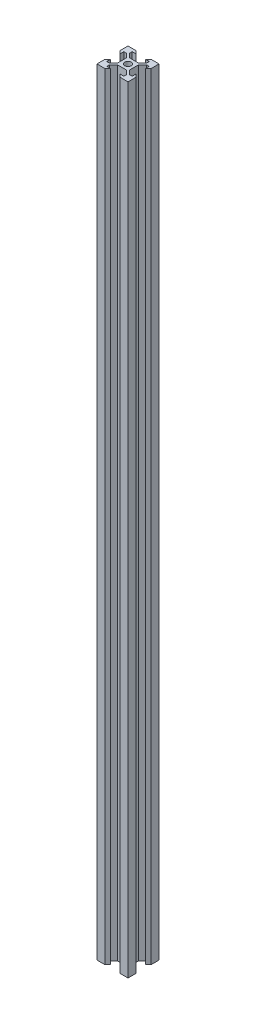
SolidWorks part; units mm, degrees
ref_plane "Front Plane" through (0, 0, 0) normal (0, 0, 1) x (1, 0, 0)
ref_plane "Top Plane" through (0, 0, 0) normal (0, 1, 0) x (1, 0, 0)
ref_plane "Right Plane" through (0, 0, 0) normal (1, 0, 0) x (0, 0, -1)
sketch "Sketch1" plane through (0, 0, 0) normal (0, 1, 0) x (1, 0, 0)
  line L0 (3.9007, 2.84) -> (2.84, 3.9007) construction
  line L1 (-10, -10) -> (10, -10) construction
  line L2 (-10, -10) -> (-10, 10) construction
  line L3 (-10, 10) -> (10, 10) construction
  line L4 (10, -10) -> (10, 10) construction
  line L5 (-10, -10) -> (10, 10) construction
  line L6 (-10, 10) -> (10, -10) construction
  line L7 (-2.84, -2.84) -> (2.84, -2.84) construction
  line L8 (-2.84, -2.84) -> (-2.84, 2.84) construction
  line L9 (-2.84, 2.84) -> (2.84, 2.84) construction
  line L10 (2.84, -2.84) -> (2.84, 2.84) construction
  line L11 (-2.84, -2.84) -> (2.84, 2.84) construction
  line L12 (-2.84, 2.84) -> (2.84, -2.84) construction
  line L13 (2.84, -3.9007) -> (3.9007, -2.84) construction
  line L14 (-3.9007, -2.84) -> (-2.84, -3.9007) construction
  line L15 (-2.84, 3.9007) -> (-3.9007, 2.84) construction
  line L16 (-3.1, 10) -> (3.1, 10) construction
  line L17 (-3.1, 10) -> (-3.1, 8.2) construction
  line L18 (-3.1, 8.2) -> (-4.9, 10)
  line L19 (3.1, 8.2) -> (3.1, 10) construction
  line L20 (-3.1, 8.2) -> (-8.2, 8.2) construction
  line L21 (-2.84, 3.9007) -> (-7.1393, 8.2) construction
  line L22 (-5.4993, 8.2) -> (-5.4993, 6.56)
  line L23 (-4.9, 10) -> (-10, 10)
  line L24 (-3.9007, -3.9007) -> (3.9007, -3.9007) construction
  line L25 (-3.9007, -3.9007) -> (-3.9007, 3.9007) construction
  line L26 (-3.9007, 3.9007) -> (3.9007, 3.9007) construction
  line L27 (3.9007, -3.9007) -> (3.9007, 3.9007) construction
  line L28 (-3.9007, -3.9007) -> (3.9007, 3.9007) construction
  line L29 (-3.9007, 3.9007) -> (3.9007, -3.9007) construction
  line L30 (-5.4993, 6.56) -> (-2.84, 3.9007)
  line L31 (-2.84, 3.9007) -> (0, 3.9007)
  line L32 (-5.4993, 8.2) -> (-3.1, 8.2)
  line L33 (-3.9007, 2.84) -> (-3.9007, 0)
  line L34 (-6.56, 5.4993) -> (-3.9007, 2.84)
  line L35 (-8.2, 5.4993) -> (-6.56, 5.4993)
  line L36 (-8.2, 5.4993) -> (-8.2, 3.1)
  line L37 (-8.2, 3.1) -> (-10, 4.9)
  line L38 (-10, 4.9) -> (-10, 10)
  line L39 (2.84, 3.9007) -> (0, 3.9007)
  line L40 (5.4993, 6.56) -> (2.84, 3.9007)
  line L41 (5.4993, 8.2) -> (5.4993, 6.56)
  line L42 (5.4993, 8.2) -> (3.1, 8.2)
  line L43 (3.1, 8.2) -> (4.9, 10)
  line L44 (4.9, 10) -> (10, 10)
  line L45 (10, 4.9) -> (10, 10)
  line L46 (8.2, 3.1) -> (10, 4.9)
  line L47 (8.2, 5.4993) -> (8.2, 3.1)
  line L48 (8.2, 5.4993) -> (6.56, 5.4993)
  line L49 (6.56, 5.4993) -> (3.9007, 2.84)
  line L50 (3.9007, 2.84) -> (3.9007, 0)
  line L51 (3.9007, -2.84) -> (3.9007, 0)
  line L52 (6.56, -5.4993) -> (3.9007, -2.84)
  line L53 (8.2, -5.4993) -> (6.56, -5.4993)
  line L54 (8.2, -5.4993) -> (8.2, -3.1)
  line L55 (8.2, -3.1) -> (10, -4.9)
  line L56 (10, -4.9) -> (10, -10)
  line L57 (4.9, -10) -> (10, -10)
  line L58 (3.1, -8.2) -> (4.9, -10)
  line L59 (5.4993, -8.2) -> (3.1, -8.2)
  line L60 (5.4993, -8.2) -> (5.4993, -6.56)
  line L61 (5.4993, -6.56) -> (2.84, -3.9007)
  line L62 (2.84, -3.9007) -> (0, -3.9007)
  line L63 (-2.84, -3.9007) -> (0, -3.9007)
  line L64 (-5.4993, -6.56) -> (-2.84, -3.9007)
  line L65 (-5.4993, -8.2) -> (-5.4993, -6.56)
  line L66 (-5.4993, -8.2) -> (-3.1, -8.2)
  line L67 (-3.1, -8.2) -> (-4.9, -10)
  line L68 (-4.9, -10) -> (-10, -10)
  line L69 (-10, -4.9) -> (-10, -10)
  line L70 (-8.2, -3.1) -> (-10, -4.9)
  line L71 (-8.2, -5.4993) -> (-8.2, -3.1)
  line L72 (-8.2, -5.4993) -> (-6.56, -5.4993)
  line L73 (-6.56, -5.4993) -> (-3.9007, -2.84)
  line L74 (-3.9007, -2.84) -> (-3.9007, 0)
  circle A0 centre (0, 0) radius 2.1
  circle A1 centre (0, 0) radius 2.1
  circle A2 centre (0, 0) radius 2.1
  circle A3 centre (0, 0) radius 2.1
  point P0 (0, 0)
  point P15 (3.3703, 3.3703)
  point P27 (0, 0)
  point P28 (0, 10)
  point P87 (0, 0)
  dimension "D2" = 4.2
  dimension "D1" = 20
  dimension "D3" = 5.68
  dimension "D4" = 1.5
  dimension "D6" = 6.2
  dimension "D7" = 1.8
  dimension "D8" = 45
  dimension "D9" = 1.64
  dimension "D10" = 4
  dimension "D11" = 90
  dimension "D12" = 1.64
  dimension "D13" = 20
  dimension "D14" = 1.5
  dimension "D15" = 5.68
  dimension "D16" = 6.2
  dimension "D17" = 1.8
  dimension "D5" = 4
extrude "Boss-Extrude1" add sketch "Sketch1" along normal blind 500 contours L74 L73 L72 L71 L70 L69 L68 L67 L66 L65 L64 L63 L62 L61 L60 L59 L58 L57 L56 L55 L54 L53 L52 L51 L50 L49 L48 L47 L46 L45 L44 L43 L42 L41 L40 L39 L31 L30 L22 L32 L18 L23 L38 L37 L36 L35 L34 L33 A0
